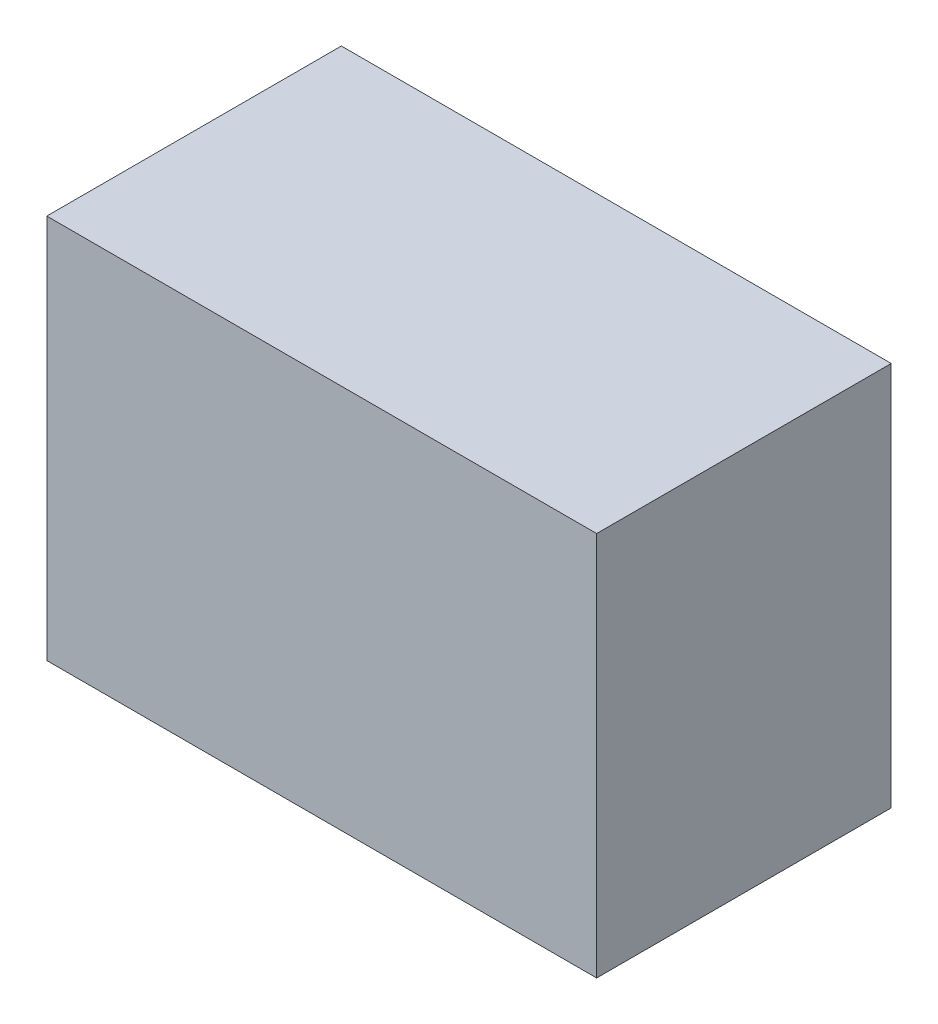
SolidWorks part; units mm, degrees
ref_plane "Front Plane" through (0, 0, 0) normal (0, 0, 1) x (1, 0, 0)
ref_plane "Top Plane" through (0, 0, 0) normal (0, 1, 0) x (1, 0, 0)
ref_plane "Right Plane" through (0, 0, 0) normal (1, 0, 0) x (0, 0, -1)
sketch "Sketch1" plane through (0, 0, 0) normal (0, 1, 0) x (1, 0, 0)
  line L1 (-70, 37.5) -> (70, 37.5)
  line L2 (-70, 37.5) -> (-70, -37.5)
  line L3 (-70, -37.5) -> (70, -37.5)
  line L4 (70, 37.5) -> (70, -37.5)
  line L5 (-70, 37.5) -> (70, -37.5) construction
  line L6 (-70, -37.5) -> (70, 37.5) construction
  point P0 (0, 0)
  dimension "D1" = 140
  dimension "D2" = 75
extrude "Boss-Extrude1" add sketch "Sketch1" along normal mid plane 98
